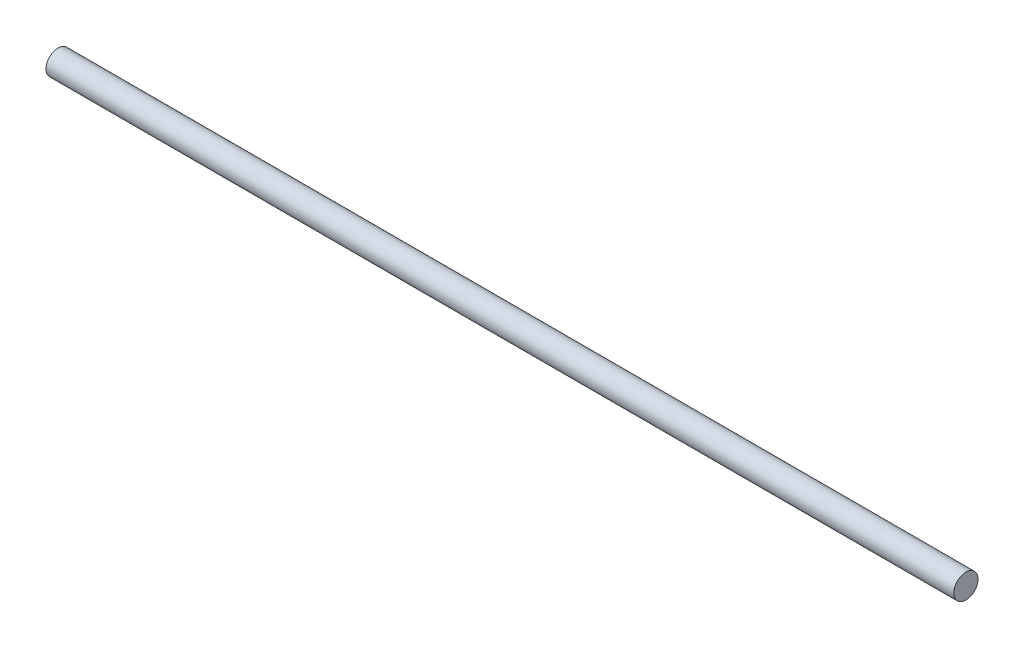
SolidWorks part; units mm, degrees
ref_plane "前视基准面" through (0, 0, 0) normal (0, 0, 1) x (1, 0, 0)
ref_plane "上视基准面" through (0, 0, 0) normal (0, 1, 0) x (1, 0, 0)
ref_plane "右视基准面" through (0, 0, 0) normal (1, 0, 0) x (0, 0, -1)
other "Configuration Table"
sketch "草图1" plane through (0, 0, 0) normal (1, 0, 0) x (0, 0, -1)
  circle A0 centre (0, 0) radius 2
  dimension "D1" = 4
extrude "凸台-拉伸1" add sketch "草图1" along normal blind 150
